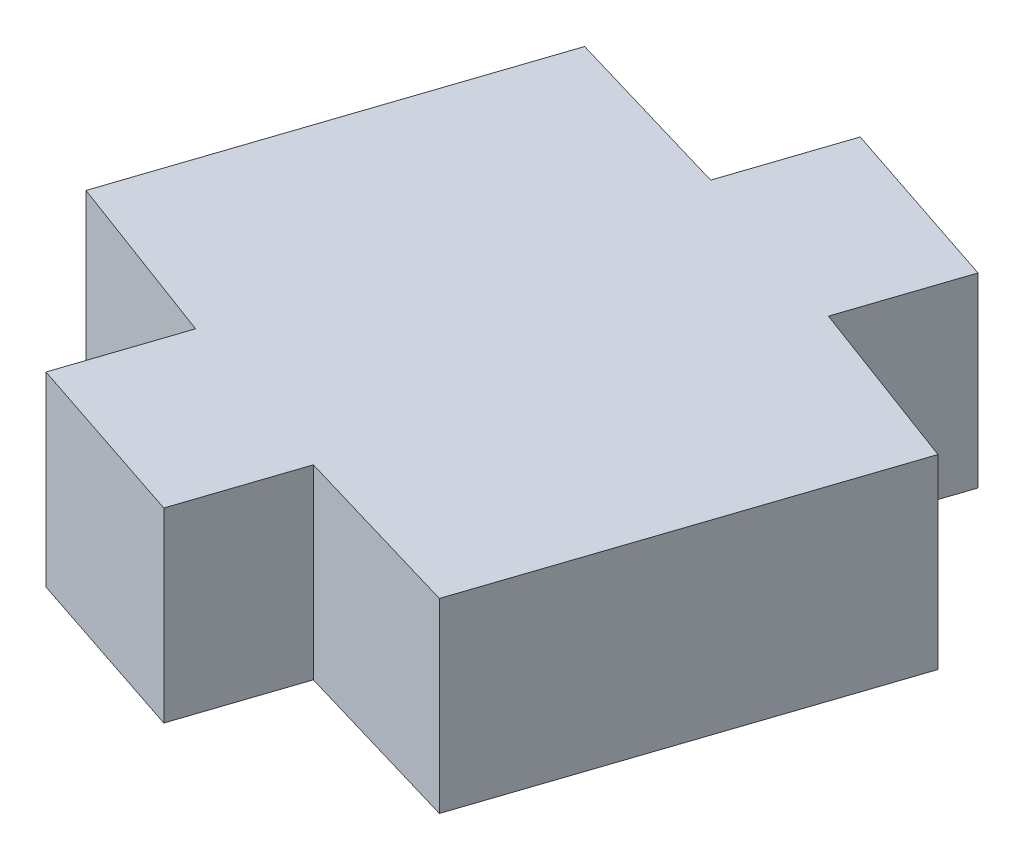
SolidWorks part; units mm, degrees
ref_plane "Front Plane" through (0, 0, 0) normal (0, 0, 1) x (1, 0, 0)
ref_plane "Top Plane" through (0, 0, 0) normal (0, 1, 0) x (1, 0, 0)
ref_plane "Right Plane" through (0, 0, 0) normal (1, 0, 0) x (0, 0, -1)
ref_plane "Plane1" through (0, 228.6, 0) normal (0, 1, 0) x (1, 0, 0)
sketch "Sketch1" plane through (0, 228.6, 0) normal (0, 1, 0) x (1, 0, 0)
  line L0 (-40.1428, 79.5583) -> (-67.1493, -1.461) construction
  line L1 (-34.4507, 77.661) -> (-61.4572, -3.3583) construction
  line L2 (-40.1428, 79.5583) -> (-67.1493, -1.461) construction
  line L3 (-34.4507, 77.661) -> (-61.4572, -3.3583) construction
  line L5 (-41.2781, 57.1789) -> (-46.9702, 59.0763)
  line L6 (-46.9702, 59.0763) -> (-48.175, 55.4618)
  line L7 (-48.175, 55.4618) -> (-53.9334, 57.1604)
  line L8 (-53.9334, 57.1604) -> (-57.9495, 45.1121)
  line L9 (-57.9495, 45.1121) -> (-52.3236, 43.016)
  line L10 (-52.3236, 43.016) -> (-53.5285, 39.4015)
  line L11 (-53.5285, 39.4015) -> (-47.8364, 37.5041)
  line L12 (-47.8364, 37.5041) -> (-46.6315, 41.1186)
  line L13 (-46.6315, 41.1186) -> (-40.8732, 39.42)
  line L14 (-40.8732, 39.42) -> (-36.8571, 51.4683)
  line L15 (-36.8571, 51.4683) -> (-42.4829, 53.5644)
  line L16 (-42.4829, 53.5644) -> (-41.2781, 57.1789)
  line L17 (-45.8349, 81.4557) -> (-72.8414, 0.4364) construction
  line L18 (-28.7586, 75.7636) -> (-55.7651, -5.2557) construction
  line L20 (-72.8414, 0.4364) -> (-52.0097, 62.9315) construction
  line L21 (-72.8414, 0.4364) -> (-52.0097, 62.9315) construction
  line L22 (-37.262, 69.2272) -> (-42.9541, 71.1245) construction
  point P28 (-40.108, 70.1759)
  dimension "D1" = 92
  dimension "D2" = 12.7
  dimension "D3" = 12.7
  dimension "D4" = 3.81
extrude "Boss-Extrude1" add sketch "Sketch1" along normal mid plane 6
